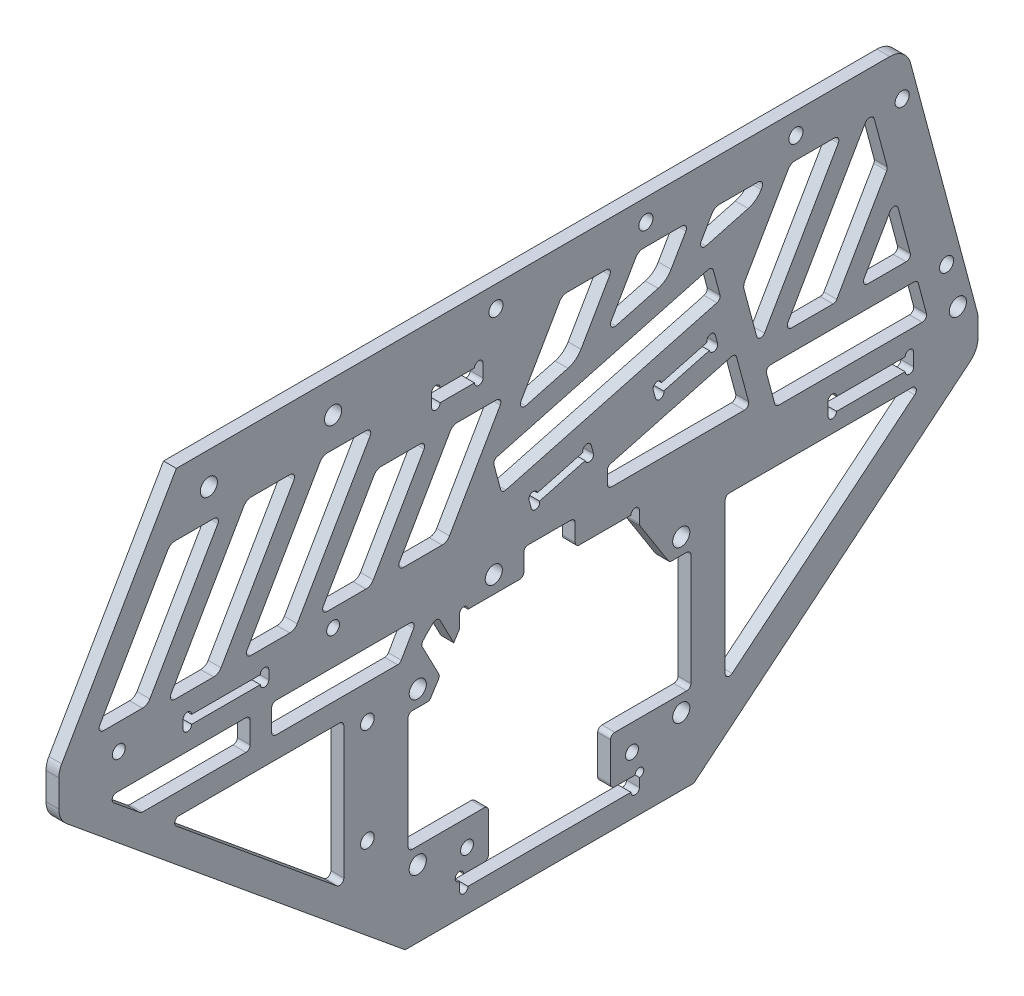
SolidWorks part; units mm, degrees
material "Thornel Mat VMA"
ref_plane "前视基准面" through (0, 0, 0) normal (0, 0, 1) x (1, 0, 0)
ref_plane "上视基准面" through (0, 0, 0) normal (0, 1, 0) x (1, 0, 0)
ref_plane "右视基准面" through (0, 0, 0) normal (1, 0, 0) x (0, 0, -1)
sketch "草图1" plane through (0, 0, 0) normal (1, 0, 0) x (0, 0, -1)
  line L0 (-33.6749, -33.5) -> (33.6749, -33.5)
  line L25 (-21, 28) -> (21, 28)
  line L26 (-21, 14) -> (-33, 14)
  line L31 (-33, 14) -> (-33, -14)
  line L38 (55, 0) -> (-55, 0) construction
  line L48 (0, 55) -> (0, -55) construction
  line L58 (-21, 14) -> (-21, 28)
  line L66 (41, 21) -> (41, -17.1265)
  line L79 (21, 14) -> (21, 28)
  line L81 (33, 14) -> (33, -14)
  line L82 (21, 14) -> (33, 14)
  line L83 (14.25, -14) -> (33, -14)
  line L84 (-21, -25) -> (-21, -28)
  line L85 (-14.25, -14) -> (-33, -14)
  line L86 (-21, -28) -> (21, -28)
  line L88 (-30.7439, 17.75) -> (0, 0) construction
  line L89 (0, 0) -> (-30.7439, -17.75) construction
  line L90 (-21, -25) -> (-14.25, -25)
  line L91 (-14.25, -25) -> (-14.25, -14)
  line L92 (21, -25) -> (21, -28)
  line L93 (21, -25) -> (14.25, -25)
  line L94 (14.25, -25) -> (14.25, -14)
  line L95 (65, 25) -> (85, 25)
  line L96 (-114.5, 33) -> (-114.5, 43)
  line L97 (82.3092, 80.5) -> (92.662, 41.863) construction
  line L98 (100, 21) -> (33.6749, -33.5)
  line L99 (41, -17.1265) -> (87.399, 21)
  line L100 (-12.5, 85.5) -> (57.5, 85.5) construction
  line L103 (-100.5, 40) -> (-50.5, 40) construction
  line L104 (-114.5, 33) -> (-33.6749, -33.5)
  line L105 (-42.5, 17) -> (-42.5, -7) construction
  line L106 (-114.5, 43) -> (-87.0759, 90.5)
  line L146 (41, 21) -> (87.399, 21)
  line L147 (65, 25) -> (65, 28)
  line L148 (65, 28) -> (85, 28)
  line L149 (85, 28) -> (85, 25)
  line L150 (100, 21) -> (100, 28)
  line L151 (100, 28) -> (84.2462, 86.7941)
  line L152 (79.4165, 90.5) -> (-87.0759, 90.5)
  line L156 (-85.5, 37) -> (-65.5, 37)
  line L157 (-85.5, 37) -> (-85.5, 39)
  line L158 (-85.5, 39) -> (-65.5, 39)
  line L159 (-65.5, 39) -> (-65.5, 37)
  circle A8 centre (0, 0) radius 35.5 construction
  circle A9 centre (-30.7439, 17.75) radius 2
  circle A11 centre (-30.7439, -17.75) radius 2
  circle A13 centre (30.7439, -17.75) radius 2
  circle A14 centre (30.7439, 17.75) radius 2
  circle A15 centre (-100.5, 40) radius 1.5
  circle A16 centre (-42.5, -7) radius 1.6
  arc A17 (84.2462, 86.7941) -> (79.4165, 90.5) centre (79.4165, 85.5) ccw
  circle A18 centre (-50.5, 40) radius 1.5
  circle A19 centre (-19.25, -20) radius 1.5
  circle A20 centre (19.25, -20) radius 1.5
  circle A21 centre (-13, 32) radius 2
  circle A22 centre (95.3047, 32) radius 2
  circle A23 centre (82.3092, 80.5) radius 1.65
  circle A24 centre (92.662, 41.863) radius 1.65
  arc A25 (-33.6749, -33.5) -> (33.6749, -33.5) centre (0, 0) ccw construction
  circle A26 centre (-12.5, 85.5) radius 1.65
  circle A27 centre (22.5, 85.5) radius 1.65
  circle A28 centre (57.5, 85.5) radius 1.65
  circle A38 centre (-42.5, 17) radius 1.6
  point P23 (0, -33.5)
  point P79 (-75.5, 40)
  point P81 (-75.5, 39)
  dimension "D3" = 56
  dimension "D17" = 65.5
  dimension "D22" = 37
  dimension "D8" = 4
  dimension "D9" = 3
  dimension "D12" = 3
  dimension "D14" = 5
  dimension "D15" = 5.5
  dimension "D16" = 26.5
  dimension "D24" = 2
  dimension "D10" = 71
  dimension "D11" = 24
  dimension "D21" = 20
  dimension "D27" = 44
  dimension "D29" = 8
  dimension "D30" = 75
  dimension "D7" = 60
  dimension "D13" = 38.5
  dimension "D18" = 3.2
  dimension "D32" = 5
  dimension "D33" = 3
  dimension "D34" = 14
  dimension "D35" = 120
  dimension "D36" = 50
  dimension "D40" = 4
  dimension "D41" = 8
  dimension "D42" = 4
  dimension "D43" = 4
  dimension "D44" = 3.5
  dimension "D47" = 3.3
  dimension "D48" = 10
  dimension "D49" = 95
  dimension "D50" = 8
  dimension "D23" = 3
  dimension "D38" = 12.5
  dimension "D52" = 9.5
  dimension "D2" = 42
  dimension "D5" = 28
  dimension "D6" = 33
  dimension "D19" = 100
  dimension "D20" = 3
  dimension "D25" = 3
  dimension "D26" = 20
  dimension "D28" = 4
  dimension "D31" = 62.5
  dimension "D39" = 10
  dimension "D45" = 40
  dimension "D46" = 3.5
  dimension "D51" = 70
  dimension "5" = 5
extrude "凸台-拉伸1" add sketch "草图1" along normal blind 3
sketch "草图5" plane through (3, 0, 0) normal (1, 0, 0) x (0, 0, -1)
  line L16 (-79.5, 83) -> (-50.5, 83) construction
  line L30 (21, 28) -> (-21, 28) construction
  line L31 (-5.43, -299.3626) -> (23.57, -299.3626) construction
  line L50 (40.0439, 61.1507) -> (-11.1502, 47.4333)
  line L51 (40.0439, 61.1507) -> (37.9733, 68.8781)
  line L52 (9.7212, 46.8141) -> (10.2389, 44.8823)
  line L53 (-4.25, 41) -> (10.2389, 44.8823)
  line L54 (-4.7676, 42.9319) -> (9.7212, 46.8141)
  line L55 (-4.25, 41) -> (-4.7676, 42.9319)
  line L59 (-11.1502, 47.4333) -> (-13.2207, 55.1607)
  line L60 (38.699, 54.5787) -> (39.2167, 52.6469)
  line L61 (24.7278, 48.7646) -> (39.2167, 52.6469)
  line L62 (24.2101, 50.6964) -> (38.699, 54.5787)
  line L63 (24.7278, 48.7646) -> (24.2101, 50.6964)
  line L64 (37.9733, 68.8781) -> (-13.2207, 55.1607)
  line L69 (79.4165, 90.5) -> (-87.0759, 90.5) construction
  line L73 (-27.5, 73) -> (-15.5, 73)
  line L74 (-15.5, 73) -> (-15.5, 76)
  line L75 (-15.5, 76) -> (-27.5, 76)
  line L76 (-27.5, 76) -> (-27.5, 73)
  line L77 (0, 0) -> (0, 90.5) construction
  line L78 (79.4165, 90.5) -> (-87.0759, 90.5) construction
  circle A0 centre (23.57, -299.3626) radius 2
  circle A1 centre (-5.43, -299.3626) radius 2
  circle A4 centre (-50.5, 83) radius 2
  circle A5 centre (-79.5, 83) radius 2
  dimension "D8" = 15
  dimension "D16" = 4
  dimension "D18" = 7.5
  dimension "D19" = 4
  dimension "D20" = 23
  dimension "D2" = 3
  dimension "D3" = 15.5
  dimension "D4" = 12
  dimension "D5" = 13
  dimension "D6" = 14.5
  dimension "D7" = 15
  dimension "D9" = 2
  dimension "D10" = 15
  dimension "D11" = 6
  dimension "D12" = 5
  dimension "D13" = 53
  dimension "D14" = 8
  dimension "D15" = 29
  dimension "D17" = 29
  dimension "D21" = 4.25
extrude "切除-拉伸2" cut sketch "草图5" against normal through all
sketch "草图6" plane through (3, 0, 0) normal (1, 0, 0) x (0, 0, -1)
  line L0 (-85.5, 39) -> (-65.5, 39) construction
  line L1 (9.7212, 46.8141) -> (-4.7676, 42.9319) construction
  line L2 (21, 28) -> (-21, 28) construction
  line L3 (-4.25, 41) -> (10.2389, 44.8823) construction
  line L4 (1.65, 0) -> (-1.65, 0) construction
  line L5 (38.699, 54.5787) -> (24.2101, 50.6964) construction
  line L6 (24.7278, 48.7646) -> (39.2167, 52.6469) construction
  line L7 (24.7278, 48.7646) -> (26.6596, 49.2822)
  line L8 (38.699, 54.5787) -> (36.7672, 54.0611)
  line L9 (9.7212, 46.8141) -> (7.7894, 46.2965)
  line L10 (-4.25, 41) -> (-2.3181, 41.5176)
  line L11 (-2.8358, 43.4495) -> (-4.7676, 42.9319)
  line L12 (8.307, 44.3646) -> (10.2389, 44.8823)
  line L13 (26.142, 51.2141) -> (24.2101, 50.6964)
  line L14 (37.2848, 52.1292) -> (39.2167, 52.6469)
  line L15 (85, 28) -> (65, 28) construction
  line L16 (65, 25) -> (85, 25) construction
  line L17 (-15.5, 76) -> (-27.5, 76) construction
  line L18 (-27.5, 73) -> (-15.5, 73) construction
  line L19 (-85.5, 37) -> (-65.5, 37) construction
  line L20 (-65.5, 39) -> (-85.5, 39) construction
  line L21 (-85.5, 37) -> (-83.5, 37)
  line L22 (-65.5, 39) -> (-67.5, 39)
  line L23 (-83.5, 39) -> (-85.5, 39)
  line L24 (-67.5, 37) -> (-65.5, 37)
  circle A2 centre (-20, 28) radius 1
  circle A4 centre (20, 28) radius 1
  circle A6 centre (20, -28) radius 1
  circle A7 centre (-20, -28) radius 1
  arc A8 (-83.5, 39) -> (-85.5, 39) centre (-84.5, 39) ccw
  arc A9 (-65.5, 39) -> (-67.5, 39) centre (-66.5, 39) ccw
  arc A10 (-2.8358, 43.4495) -> (-4.7676, 42.9319) centre (-3.8017, 43.1907) ccw
  arc A11 (-4.25, 41) -> (-2.3181, 41.5176) centre (-3.2841, 41.2588) ccw
  arc A12 (9.7212, 46.8141) -> (7.7894, 46.2965) centre (8.7553, 46.5553) ccw
  arc A13 (8.307, 44.3646) -> (10.2389, 44.8823) centre (9.273, 44.6235) ccw
  arc A14 (26.142, 51.2141) -> (24.2101, 50.6964) centre (25.1761, 50.9552) ccw
  arc A15 (24.7278, 48.7646) -> (26.6596, 49.2822) centre (25.6937, 49.0234) ccw
  arc A16 (38.699, 54.5787) -> (36.7672, 54.0611) centre (37.7331, 54.3199) ccw
  arc A17 (37.2848, 52.1292) -> (39.2167, 52.6469) centre (38.2507, 52.388) ccw
  circle A18 centre (66, 28) radius 1
  circle A19 centre (66, 25) radius 1
  circle A20 centre (84, 28) radius 1
  circle A21 centre (84, 25) radius 1
  circle A22 centre (-26.5, 76) radius 1
  circle A23 centre (-26.5, 73) radius 1
  circle A24 centre (-16.5, 76) radius 1
  circle A25 centre (-16.5, 73) radius 1
  circle A26 centre (-21, -25) radius 1
  circle A27 centre (21, -25) radius 1
  arc A28 (-85.5, 37) -> (-83.5, 37) centre (-84.5, 37) ccw
  arc A29 (-67.5, 37) -> (-65.5, 37) centre (-66.5, 37) ccw
  dimension "D1" = 2
extrude "切除-拉伸3" cut sketch "草图6" against normal through all
chamfer "倒角1" distance 7 distance2 11 1 edges at (1.5, 14, 21)
sketch "草图7" plane through (3, 0, 0) normal (1, 0, 0) x (0, 0, -1)
  line L37 (-53.6781, 44) -> (-41.6794, 44)
  line L42 (-53.6781, 44) -> (-40.399, 67)
  line L48 (-105.8397, 46) -> (-93.8411, 46)
  line L49 (-105.8397, 46) -> (-88.5192, 76)
  line L59 (-59.4516, 44) -> (-40.9763, 76)
  line L61 (-41.6794, 44) -> (-28.4004, 67)
  line L62 (-40.399, 67) -> (-28.4004, 67)
  line L63 (-23.9073, 44) -> (-35.9059, 44)
  line L64 (-23.9073, 44) -> (-10.6282, 67)
  line L65 (-35.9059, 44) -> (-22.6269, 67)
  line L68 (-7.8745, 61.7696) -> (2.9395, 80.5)
  line L69 (6.32, 65.573) -> (14.9381, 80.5)
  line L72 (13.1502, 67.4032) -> (20.7116, 80.5)
  line L73 (27.3447, 71.2066) -> (32.7102, 80.5)
  line L80 (34.1748, 73.0367) -> (38.4838, 80.5)
  line L85 (48.3693, 76.8401) -> (50.4824, 80.5)
  line L89 (45.1773, 61.3113) -> (56.2559, 80.5)
  line L92 (48.9807, 47.1167) -> (68.2545, 80.5)
  line L95 (-52.975, 76) -> (-40.9763, 76)
  line L96 (54.7542, 47.1167) -> (66.7528, 47.1167)
  line L97 (54.7542, 47.1167) -> (74.028, 80.5)
  line L98 (66.7528, 47.1167) -> (78.8914, 68.1414)
  line L100 (72.5263, 47.1167) -> (84.5249, 47.1167)
  line L101 (72.5263, 47.1167) -> (80.7215, 61.3113)
  line L104 (2.9395, 80.5) -> (14.9381, 80.5)
  line L105 (-10.6282, 67) -> (-22.6269, 67)
  line L106 (-25.5, 73) -> (-17.5, 73) construction
  line L107 (20.7116, 80.5) -> (32.7102, 80.5)
  line L108 (-103.841, 32) -> (-95.3331, 25)
  line L109 (38.4838, 80.5) -> (50.4824, 80.5)
  line L110 (56.2559, 80.5) -> (68.2545, 80.5)
  line L111 (74.028, 80.5) -> (75.5799, 80.5)
  line L112 (84.5249, 47.1167) -> (80.7215, 61.3113)
  line L113 (6.32, 65.573) -> (-7.8745, 61.7696)
  line L114 (36.6792, 73.7078) -> (-14.5148, 59.9903)
  line L115 (48.3693, 76.8401) -> (34.1748, 73.0367)
  line L116 (-89.2223, 44) -> (-77.2237, 44)
  line L117 (-77.2237, 44) -> (-58.7485, 76)
  line L119 (27.3447, 71.2066) -> (13.1502, 67.4032)
  line L120 (-95.3331, 25) -> (-69.8383, 25)
  line L121 (-69.8383, 25) -> (-69.8383, 32)
  line L122 (-69.8383, 32) -> (-103.841, 32)
  line L123 (-64.8383, 32) -> (-64.8383, 25)
  line L124 (-64.8383, 25) -> (-34.877, 25)
  line L125 (100, 28) -> (84.2462, 86.7941) construction
  line L126 (78.8914, 68.1414) -> (75.5799, 80.5)
  line L127 (-34.877, 25) -> (-30.8355, 32)
  line L128 (-30.8355, 32) -> (-64.8383, 32)
  line L129 (45.1773, 61.3113) -> (48.9807, 47.1167)
  line L130 (40.0439, 61.1507) -> (37.9733, 68.8781) construction
  line L135 (13.5, 40.5797) -> (43.4085, 48.5937)
  line L136 (43.4085, 48.5937) -> (46.783, 36)
  line L137 (46.783, 36) -> (13.5, 36)
  line L138 (26.6596, 49.2822) -> (37.2848, 52.1292) construction
  line L139 (19, 28) -> (-19, 28) construction
  line L140 (-87.0759, 90.5) -> (-114.5, 43) construction
  line L141 (52.7632, 33) -> (88.3075, 33)
  line L142 (52.7632, 33) -> (50.3204, 42.1167)
  line L143 (88.3075, 33) -> (85.8647, 42.1167)
  line L144 (50.3204, 42.1167) -> (85.8647, 42.1167)
  line L145 (83, 28) -> (67, 28) construction
  line L146 (-28, 14) -> (-21, 25) construction
  line L148 (-67.5, 39) -> (-83.5, 39) construction
  line L149 (100, 28) -> (84.2462, 86.7941) construction
  line L150 (13.5, 40.5797) -> (13.5, 36)
  line L154 (79.4165, 90.5) -> (-87.0759, 90.5) construction
  line L156 (-89.2561, 20) -> (-48, 20)
  line L157 (-48, 20) -> (-48, -13.944)
  line L158 (-48, -13.944) -> (-89.2561, 20)
  line L160 (-83.5, 37) -> (-67.5, 37) construction
  line L161 (-114.5, 33) -> (-33.6749, -33.5) construction
  line L162 (-33, 14) -> (-33, -14) construction
  line L163 (-6, 28) -> (6, 28)
  line L164 (-22.3422, 22.8908) -> (-25.5574, 29.0596)
  line L165 (-29.6938, 25.7534) -> (-25.5634, 17.8289)
  line L166 (-25.5634, 17.8289) -> (-22.3422, 22.8908)
  line L167 (-6, 28) -> (-6, 34)
  line L168 (-6, 34) -> (6, 34)
  line L169 (6, 28) -> (6, 34)
  line L170 (0, 0) -> (0, 34) construction
  line L171 (-88.5192, 76) -> (-76.5206, 76)
  line L172 (-76.5206, 76) -> (-93.8411, 46)
  line L173 (-89.2223, 44) -> (-70.7471, 76)
  line L174 (-70.7471, 76) -> (-58.7485, 76)
  line L175 (-52.975, 76) -> (-71.4502, 44)
  line L176 (-71.4502, 44) -> (-59.4516, 44)
  circle A1 centre (-100.5, 40) radius 1.5 construction
  arc A2 (-27.1231, 29.3316) -> (-29.5466, 26.8887) centre (0, 0) ccw
  circle A3 centre (-79.5, 83) radius 2 construction
  arc A5 (-25.5574, 29.0596) -> (-27.1231, 29.3316) centre (-26.4441, 28.5974) ccw
  arc A6 (-29.5466, 26.8887) -> (-29.6938, 25.7534) centre (-28.807, 26.2156) ccw
  dimension "D18" = 5
  dimension "D9" = 6
  dimension "D35" = 39.95
  dimension "D36" = 1
  dimension "D5" = 10
  dimension "D6" = 6
  dimension "D7" = 5
  dimension "D8" = 5
  dimension "D10" = 8
  dimension "D11" = 5
  dimension "D12" = 6
  dimension "D13" = 5
  dimension "D14" = 17
  dimension "D15" = 5
  dimension "D16" = 5
  dimension "D17" = 7
  dimension "D19" = 5
  dimension "D21" = 5
  dimension "D22" = 5
  dimension "D23" = 5
  dimension "D24" = 5
  dimension "D25" = 5
  dimension "D26" = 5
  dimension "D28" = 5
  dimension "D29" = 10
  dimension "D30" = 5
  dimension "D27" = 5
  dimension "D31" = 5
  dimension "D32" = 6
  dimension "D33" = 15
  dimension "D34" = 5
  dimension "D37" = 60
  dimension "D38" = 2.5
  dimension "D39" = 6
  dimension "D40" = 12
  dimension "D41" = 7.5
  dimension "D42" = 6
extrude "切除-拉伸4" cut sketch "草图7" against normal through all
chamfer "倒角2" distance 11 distance2 7 1 edges at (1.5, 14, -21)
fillet "圆角1" radius 1 68 edges at (1.5, -14, 14.25) (1.5, -14, -14.25) (1.5, 21, -87.399) (1.5, -17.1265, -41) (1.5, 21, -41) (1.5, 14, -33) (1.5, -14, -33) (1.5, -25, -14.25) (1.5, -25, 14.25) (1.5, -14, 33) (1.5, 14, 33) (1.5, 14, 28) (1.5, 17.8289, 25.5634) (1.5, 28, 6) (1.5, 34, 6) (1.5, 34, -6) (1.5, 28, -6) (1.5, 25, -21) (1.5, 14, -28) (1.5, 47.4333, 11.1502) (1.5, 55.1607, 13.2207) (1.5, 68.8781, -37.9733) (1.5, 61.1507, -40.0439) (1.5, 61.7696, 7.8745) (1.5, 80.5, -14.9381) (1.5, 67.4032, -13.1502) (1.5, 80.5, -32.7102) (1.5, 44, 35.9059) (1.5, 67, 10.6282) (1.5, 67, 28.4004) (1.5, 44, 53.6781) (1.5, 46, 105.8397) (1.5, 76, 76.5206) (1.5, 80.5, -68.2545) (1.5, 47.1167, -48.9807) (1.5, 47.1167, -72.5263) (1.5, 61.3113, -80.7215) (1.5, 47.1167, -84.5249) (1.5, 80.5, -50.4824) (1.5, 73.0367, -34.1748) (1.5, 47.1167, -66.7528) (1.5, 47.1167, -54.7542) (1.5, 80.5, -74.028) (1.5, 80.5, -75.5799) (1.5, 68.1414, -78.8914) (1.5, 42.1167, -85.8647) (1.5, 33, -88.3075) (1.5, 33, -52.7632) (1.5, 42.1167, -50.3204) (1.5, 20, 48) (1.5, -13.944, 48) (1.5, 20, 89.2561) (1.5, 25, 95.3331) (1.5, 32, 103.841) (1.5, 32, 69.8383) (1.5, 25, 69.8383) (1.5, 25, 34.877) (1.5, 25, 64.8383) (1.5, 32, 64.8383) (1.5, 32, 30.8355) (1.5, 44, 89.2223) (1.5, 76, 58.7485) (1.5, 76, 40.9763) (1.5, 44, 71.4502) (1.5, 36, -13.5) (1.5, 40.5797, -13.5) (1.5, 48.5937, -43.4085) (1.5, 36, -46.783)
fillet "圆角2" radius 5 7 edges at (1.5, 28, -100) (1.5, 21, -100) (1.5, 43, 114.5) (1.5, 76.8401, -48.3693) (1.5, 71.2066, -27.3447) (1.5, 65.573, -6.32) (1.5, 33, 114.5)
fillet "圆角3" radius 2 15 edges at (1.5, 46, 93.8411) (1.5, 44, 77.2237) (1.5, 44, 59.4516) (1.5, 44, 41.6794) (1.5, 44, 23.9073) (1.5, 61.3113, -45.1773) (1.5, 80.5, -56.2559) (1.5, 80.5, -38.4838) (1.5, 80.5, -20.7116) (1.5, 80.5, -2.9395) (1.5, 67, 22.6269) (1.5, 67, 40.399) (1.5, 76, 52.975) (1.5, 76, 70.7471) (1.5, 76, 88.5192)
